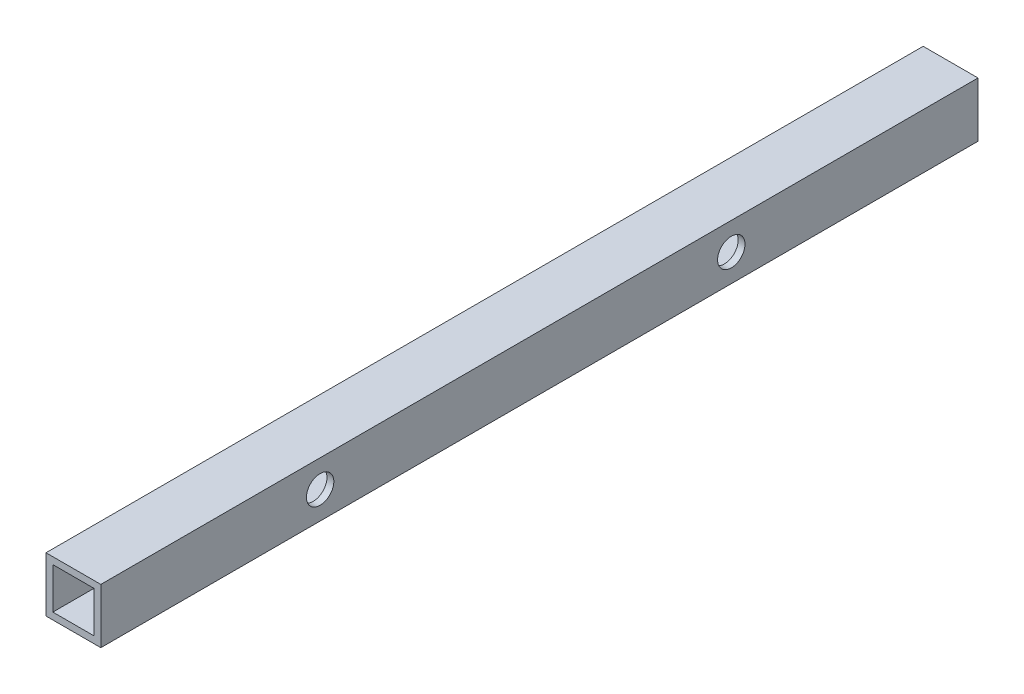
SolidWorks part; units mm, degrees
material "1060 Alloy"
ref_plane "Front Plane" through (0, 0, 0) normal (0, 0, 1) x (1, 0, 0)
ref_plane "Top Plane" through (0, 0, 0) normal (0, 1, 0) x (1, 0, 0)
ref_plane "Right Plane" through (0, 0, 0) normal (1, 0, 0) x (0, 0, -1)
sketch "Sketch1" plane through (0, 0, 0) normal (0, 0, 1) x (1, 0, 0)
  line L1 (-12.7, -12.7) -> (12.7, -12.7)
  line L2 (-12.7, -12.7) -> (-12.7, 12.7)
  line L3 (-12.7, 12.7) -> (12.7, 12.7)
  line L4 (12.7, -12.7) -> (12.7, 12.7)
  line L5 (-12.7, -12.7) -> (12.7, 12.7) construction
  line L6 (-12.7, 12.7) -> (12.7, -12.7) construction
  point P0 (0, 0)
  dimension "D1" = 25.4
extrude "Extrude-Thin1" add sketch "Sketch1" along normal blind 406.4 thin thin type one direction reverse wall 3.175
sketch "Sketch2" plane through (12.7, 0, 0) normal (1, 0, 0) x (0, 0, -1)
  line L0 (0, -12.7) -> (0, 12.7) construction
  line L1 (-406.4, -12.7) -> (-406.4, 12.7) construction
  circle A0 centre (-304.8, 0) radius 6.35
  circle A1 centre (-114.3, 0) radius 6.35
  dimension "D1" = 12.7
  dimension "D2" = 114.3
  dimension "D3" = 101.6
extrude "Cut-Extrude1" cut sketch "Sketch2" against normal through all
